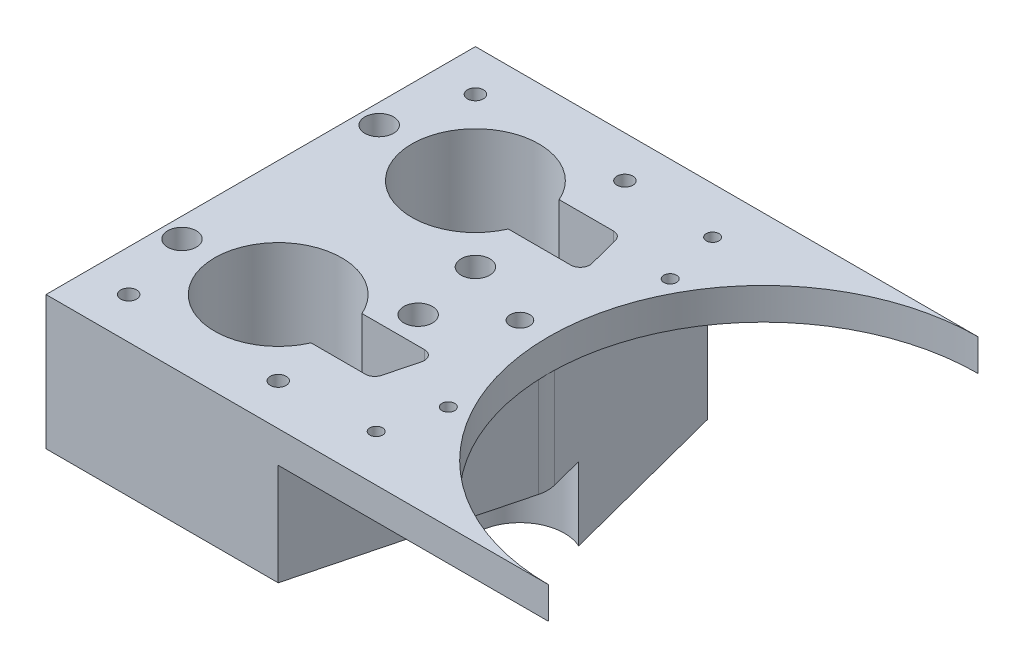
SolidWorks part; units mm, degrees
ref_plane "Alzado" through (0, 0, 0) normal (0, 0, 1) x (1, 0, 0)
ref_plane "Planta" through (0, 0, 0) normal (0, 1, 0) x (1, 0, 0)
ref_plane "Vista lateral" through (0, 0, 0) normal (1, 0, 0) x (0, 0, -1)
sketch "Croquis2" plane through (0, 0, 0) normal (0, 1, 0) x (1, 0, 0)
  line L0 (32.725, -35) -> (-35, -35) construction
  line L1 (52.1828, -19.7053) -> (38, 35) construction
  line L2 (-35, 35) -> (38, 35) construction
  line L3 (-35, -35) -> (-35, 35) construction
  line L4 (32.725, -35) -> (-35, -35)
  line L5 (52.1828, -19.7053) -> (38, 35)
  line L6 (-35, 35) -> (38, 35)
  line L7 (-35, -35) -> (-35, 35)
  arc A0 (32.5, -32.5) -> (54.1538, -20.7774) centre (46.5, -32.5) ccw construction
  arc A1 (52.1828, -19.7053) -> (32.5, -32.5) centre (46.5, -32.5) ccw construction
  arc A2 (32.5, -32.5) -> (32.725, -35) centre (46.5, -32.5) ccw
  arc A3 (52.1828, -19.7053) -> (32.5, -32.5) centre (46.5, -32.5) ccw
  circle A4 centre (1.5, -1.5) radius 24 construction
  circle A5 centre (1.5, -1.5) radius 24 construction
extrude "Saliente-Extruir2" add sketch "Croquis2" along normal blind 23
sketch "Croquis7" plane through (0, 23, 0) normal (0, 1, 0) x (1, 0, 0)
  circle A0 centre (1.5, -1.5) radius 24 construction
  circle A1 centre (1.5, -1.5) radius 24 construction
  circle A2 centre (1.5, -1.5) radius 20
  dimension "D1" = 40
extrude "Cortar-Extruir1" cut sketch "Croquis7" against normal blind 16 contours A2
sketch "Croquis8" plane through (0, 7, 0) normal (0, 1, 0) x (1, 0, 0)
  circle A0 centre (1.5, -1.5) radius 10.25
  circle A1 centre (1.5, -1.5) radius 20 construction
  dimension "D1" = 20.5
extrude "Cortar-Extruir2" cut sketch "Croquis8" against normal through all
sketch "Croquis9" plane through (0, 23, 0) normal (0, 1, 0) x (1, 0, 0)
  line L0 (-35, 35) -> (-35, -35) construction
  line L1 (38, 35) -> (-35, 35) construction
  line L2 (-35, 35) -> (-35, -100)
  line L4 (38, 35) -> (-35, 35)
  line L6 (46.5, -32.5) -> (-35, -32.5) construction
  line L7 (38, 35) -> (54.8494, -29.9904)
  line L9 (52.1828, -19.7053) -> (38, 35) construction
  line L10 (38, -100) -> (54.8494, -35.0096)
  line L11 (38, -100) -> (-35, -100)
  arc A0 (52.1828, -19.7053) -> (32.725, -35) centre (46.5, -32.5) ccw construction
  circle A2 centre (1.5, -1.5) radius 20 construction
  circle A3 centre (1.5, -1.5) radius 20
  arc A4 (52.1828, -19.7053) -> (32.725, -35) centre (46.5, -32.5) ccw construction
  circle A5 centre (46.5, -32.5) radius 3.075
  arc A6 (54.8494, -35.0096) -> (54.8494, -29.9904) centre (45.1694, -32.5) ccw
  circle A7 centre (1.5, -1.5) radius 10.25 construction
  circle A8 centre (1.5, -1.5) radius 10.25 construction
  circle A9 centre (1.5, -63.5) radius 10.25
  point P19 (55.5, -32.5)
  dimension "D1" = 10
  dimension "D2" = 6.15
extrude "Saliente-Extruir3" add sketch "Croquis9" along normal blind 32
sketch "Croquis10" plane through (0, 23, 0) normal (0, -1, 0) x (1, 0, 0)
  line L0 (46.5, 32.5) -> (-35, 32.5) construction
  line L1 (-35, -35) -> (-35, 35) construction
  circle A0 centre (1.5, 1.5) radius 20 construction
  circle A1 centre (1.5, 1.5) radius 20 construction
  circle A2 centre (1.5, 63.5) radius 20
extrude "Cortar-Extruir3" cut sketch "Croquis10" against normal through all from offset 7 offset against normal yes
sketch "Croquis11" plane through (0, 55, 0) normal (0, 1, 0) x (1, 0, 0)
  line L0 (46.5, -32.5) -> (123, -32.5) construction
  line L1 (38, 35) -> (-35, 35) construction
  line L2 (123, 35) -> (-35, 35)
  line L3 (-35, 35) -> (-35, -100)
  line L4 (-35, -100) -> (123, -100)
  arc A0 (123, -100) -> (123, 35) centre (123, -32.5) ccw
  circle A1 centre (46.5, -32.5) radius 3.075 construction
  circle A2 centre (1.5, -63.5) radius 20 construction
  circle A3 centre (1.5, -1.5) radius 20 construction
  circle A4 centre (46.5, -32.5) radius 3.075
  circle A5 centre (1.5, -63.5) radius 20
  circle A6 centre (1.5, -1.5) radius 20
  dimension "D1" = 76.5
extrude "Saliente-Extruir4" add sketch "Croquis11" along normal blind 20
sketch "Croquis12" plane through (0, 55, 0) normal (0, -1, 0) x (1, 0, 0)
  circle A0 centre (123, 32.5) radius 63
  dimension "D1" = 126
extrude "Cortar-Extruir4" cut sketch "Croquis12" against normal blind 3
sketch "Croquis13" plane through (0, 58, 0) normal (0, -1, 0) x (1, 0, 0)
  circle A0 centre (123, 32.5) radius 55
  circle A1 centre (123, 32.5) radius 63 construction
  dimension "D1" = 110
extrude "Cortar-Extruir5" cut sketch "Croquis13" against normal blind 10
sketch "Croquis14" plane through (0, 75, 0) normal (0, 1, 0) x (1, 0, 0)
  line L0 (-35, -100) -> (123, -100) construction
  line L1 (123, 35) -> (-35, 35) construction
  line L2 (-35, 35) -> (-35, -100) construction
  line L3 (-35, -100) -> (123, -100)
  line L4 (123, 35) -> (-35, 35)
  line L5 (-35, 35) -> (-35, -100)
  arc A0 (123, -100) -> (123, 35) centre (123, -32.5) ccw construction
  arc A1 (123, -100) -> (123, 35) centre (123, -32.5) ccw
extrude "Saliente-Extruir5" add sketch "Croquis14" along normal blind 10
chamfer "Chaflán1" distance 8 angle 30 3 edges at (44, 85, -35) (190.5, 85, 32.5) (44, 85, 100)
sketch "Croquis15" plane through (0, 68, 0) normal (0, -1, 0) x (1, 0, 0)
  circle A0 centre (123, 32.5) radius 6
  dimension "D1" = 12
extrude "Cortar-Extruir6" cut sketch "Croquis15" against normal blind 14.8
sketch "Croquis17" plane through (0, 0, 0) normal (0, -1, 0) x (1, 0, 0)
  line L0 (1.5, 1.5) -> (16.5, 1.5) construction
  line L1 (1.5, 1.5) -> (13.6244, 8.5) construction
  circle A0 centre (1.5, 1.5) radius 15 construction
  circle A1 centre (1.5, 1.5) radius 14 construction
  circle A2 centre (16.5, 1.5) radius 1.5
  circle A3 centre (-6, -11.4904) radius 1.5
  circle A4 centre (-6, 14.4904) radius 1.5
  circle A6 centre (13.6244, 8.5) radius 1.5
  circle A7 centre (1.5, -12.5) radius 1.5
  circle A8 centre (1.5, 1.5) radius 14 construction
  circle A9 centre (-10.6244, 8.5) radius 1.5
  circle A10 centre (1.5, 1.5) radius 14 construction
  point P13 (1.5, 1.5)
  point P22 (1.5, 1.5)
  dimension "D1" = 30
  dimension "D2" = 28
  dimension "D3" = 3
  dimension "D5" = 30
  dimension "D4" = 3
  dimension "D6" = 3
extrude "Cortar-Extruir7" cut sketch "Croquis17" against normal up to next
sketch "Croquis19" plane through (0, 23, 0) normal (0, -1, 0) x (1, 0, 0)
  line L0 (1.5, 63.5) -> (16.5, 63.5) construction
  line L1 (1.5, 63.5) -> (13.6244, 70.5) construction
  circle A0 centre (1.5, 63.5) radius 15 construction
  circle A1 centre (1.5, 63.5) radius 14 construction
  circle A2 centre (16.5, 63.5) radius 1.5
  circle A3 centre (-6, 50.5096) radius 1.5
  circle A4 centre (-6, 76.4904) radius 1.5
  circle A6 centre (13.6244, 70.5) radius 1.5
  circle A7 centre (1.5, 49.5) radius 1.5
  circle A8 centre (-10.6244, 70.5) radius 1.5
  point P13 (1.5, 63.5)
  point P20 (1.5, 63.5)
  dimension "D1" = 30
  dimension "D2" = 28
  dimension "D3" = 3
  dimension "D6" = 30
  dimension "D4" = 3
  dimension "D5" = 3
extrude "Cortar-Extruir9" cut sketch "Croquis19" against normal up to next
sketch "Croquis20" plane through (0, 0, 0) normal (0, -1, 0) x (1, 0, 0)
  line L1 (16.5, 1.5) -> (41.2646, 1.5) construction
  line L2 (46.3749, 21.211) -> (32.192, -33.4942)
  line L3 (42.3657, 5.7471) -> (39.7731, -4.2529)
  line L4 (39.4617, 9.5) -> (19.8303, 9.5)
  line L5 (36.8691, -6.5) -> (19.8303, -6.5)
  circle A0 centre (1.5, 1.5) radius 20 construction
  arc A1 (19.8303, -6.5) -> (19.8303, 9.5) centre (1.5, 1.5) ccw
  arc A2 (39.7731, -4.2529) -> (36.8691, -6.5) centre (36.8691, -3.5) cw
  arc A3 (42.3657, 5.7471) -> (39.4617, 9.5) centre (39.4617, 6.5) ccw
  dimension "D3" = 3
  dimension "D2" = 16
  dimension "D1" = 6
extrude "Cortar-Extruir10" cut sketch "Croquis20" against normal through all
sketch "Croquis21" plane through (0, 23, 0) normal (0, -1, 0) x (1, 0, 0)
  line L0 (19.8303, -6.5) -> (36.8691, -6.5) construction
  line L1 (39.7731, -4.2529) -> (42.3657, 5.7471) construction
  line L2 (39.4617, 9.5) -> (19.8303, 9.5) construction
  line L3 (19.8303, -6.5) -> (36.8691, -6.5) construction
  line L4 (39.7731, -4.2529) -> (42.3657, 5.7471) construction
  line L5 (39.4617, 9.5) -> (19.8303, 9.5) construction
  line L6 (46.5, 32.5) -> (-35, 32.5) construction
  line L7 (-35, -35) -> (-35, 35) construction
  line L8 (39.4617, 55.5) -> (19.8303, 55.5)
  line L9 (39.7731, 69.2529) -> (42.3657, 59.2529)
  line L10 (19.8303, 71.5) -> (36.8691, 71.5)
  arc A0 (36.8691, -6.5) -> (39.7731, -4.2529) centre (36.8691, -3.5) ccw construction
  arc A1 (42.3657, 5.7471) -> (39.4617, 9.5) centre (39.4617, 6.5) ccw construction
  arc A2 (19.8303, -6.5) -> (19.8303, 9.5) centre (1.5, 1.5) ccw construction
  arc A3 (36.8691, -6.5) -> (39.7731, -4.2529) centre (36.8691, -3.5) ccw construction
  arc A4 (42.3657, 5.7471) -> (39.4617, 9.5) centre (39.4617, 6.5) ccw construction
  arc A5 (19.8303, -6.5) -> (19.8303, 9.5) centre (1.5, 1.5) ccw construction
  arc A6 (19.8303, 71.5) -> (19.8303, 55.5) centre (1.5, 63.5) cw
  arc A7 (42.3657, 59.2529) -> (39.4617, 55.5) centre (39.4617, 58.5) cw
  arc A8 (36.8691, 71.5) -> (39.7731, 69.2529) centre (36.8691, 68.5) cw
extrude "Cortar-Extruir11" cut sketch "Croquis21" against normal blind 50
sketch "Croquis22" plane through (0, 0, 0) normal (0, -1, 0) x (1, 0, 0)
  circle A0 centre (-6, 14.4904) radius 3
  circle A1 centre (-10.6244, 8.5) radius 3
  circle A2 centre (-6, -11.4904) radius 3
  circle A3 centre (1.5, -12.5) radius 3
  circle A4 centre (16.5, 1.5) radius 3
  circle A5 centre (13.6244, 8.5) radius 3
  dimension "D1" = 6
extrude "Cortar-Extruir12" cut sketch "Croquis22" against normal blind 3
sketch "Croquis23" plane through (0, 23, 0) normal (0, -1, 0) x (1, 0, 0)
  circle A0 centre (-6, 76.4904) radius 3
  circle A1 centre (-10.6244, 70.5) radius 3
  circle A2 centre (-6, 50.5096) radius 3
  circle A3 centre (1.5, 49.5) radius 3
  circle A4 centre (16.5, 63.5) radius 3
  circle A5 centre (13.6244, 70.5) radius 3
  dimension "D1" = 6
extrude "Cortar-Extruir13" cut sketch "Croquis23" against normal blind 3
sketch "Croquis25" plane through (0, 23, 0) normal (0, -1, 0) x (1, 0, 0)
  line L0 (1.5, 63.5) -> (-35, 63.5) construction
  line L1 (-35, 35) -> (-35, 100) construction
  line L2 (-35, 35) -> (32.725, 35) construction
  circle A0 centre (-28.75, 63.5) radius 2.5
  circle A1 centre (29, 47) radius 2.5
  dimension "D1" = 5
  dimension "D2" = 6.25
  dimension "D3" = 64
  dimension "D4" = 12
extrude "Cortar-Extruir15" cut sketch "Croquis25" against normal through all
sketch "Croquis24" plane through (0, 0, 0) normal (0, -1, 0) x (1, 0, 0)
  line L0 (1.5, 1.5) -> (-35, 1.5) construction
  line L1 (-35, -35) -> (-35, 35) construction
  line L4 (-22, -22) -> (25, -22) construction
  line L5 (-22, -22) -> (-22, 25) construction
  line L6 (-22, 25) -> (25, 25) construction
  line L7 (25, -22) -> (25, 25) construction
  line L8 (-22, -22) -> (25, 25) construction
  line L9 (-22, 25) -> (25, -22) construction
  circle A0 centre (-28.75, 1.5) radius 2.5
  circle A1 centre (25, 25) radius 2.5
  dimension "D1" = 5
  dimension "D2" = 6.25
  dimension "D3" = 47
extrude "Cortar-Extruir14" cut sketch "Croquis24" against normal through all
sketch "Croquis26" plane through (0, 55, 0) normal (0, -1, 0) x (1, 0, 0)
  line L2 (49.616, 103.0115) -> (66.4653, 38.0212)
  line L3 (49.616, 103.0115) -> (66.4653, 38.0212) construction
  line L4 (-35, 95.3812) -> (123, 95.3812) construction
  line L5 (46.5, 32.5) -> (123, 32.5) construction
  circle A0 centre (54.1868, 85.3812) radius 2
  circle A1 centre (58.8535, 67.3812) radius 2
  circle A2 centre (58.8535, -2.3812) radius 2
  circle A3 centre (54.1868, -20.3812) radius 2
  dimension "D2" = 10
  dimension "D3" = 18
  dimension "D4" = 4
  dimension "D1" = 12
extrude "Cortar-Extruir16" cut sketch "Croquis26" against normal through all
sketch "Croquis27" plane through (0, 85, 0) normal (0, 1, 0) x (1, 0, 0)
  circle A0 centre (54.1868, 20.3812) radius 3.5
  circle A1 centre (58.8535, 2.3812) radius 3.5
  circle A2 centre (58.8535, -67.3812) radius 3.5
  circle A3 centre (54.1868, -85.3812) radius 3.5
  dimension "D1" = 7
extrude "Cortar-Extruir17" cut sketch "Croquis27" against normal blind 5
sketch "Croquis28" plane through (0, 55, 0) normal (0, -1, 0) x (1, 0, 0)
  line L0 (38, 100) -> (54.8494, 35.0096) construction
  line L1 (55.2228, 81.3853) -> (58.1654, 84.2804)
  line L2 (58.1654, 84.2804) -> (57.1294, 88.2764)
  line L3 (57.1294, 88.2764) -> (53.1508, 89.3771)
  line L4 (53.1508, 89.3771) -> (50.2082, 86.482)
  line L5 (50.2082, 86.482) -> (51.2442, 82.486)
  line L6 (51.2442, 82.486) -> (55.2228, 81.3853)
  line L7 (59.8894, 63.3853) -> (62.832, 66.2804)
  line L8 (62.832, 66.2804) -> (61.7961, 70.2764)
  line L9 (61.7961, 70.2764) -> (57.8175, 71.3771)
  line L10 (57.8175, 71.3771) -> (54.8749, 68.482)
  line L11 (54.8749, 68.482) -> (55.9109, 64.486)
  line L12 (55.9109, 64.486) -> (59.8894, 63.3853)
  line L13 (59.8894, 1.6147) -> (55.9109, 0.514)
  line L14 (55.9109, 0.514) -> (54.8749, -3.482)
  line L15 (54.8749, -3.482) -> (57.8175, -6.3771)
  line L16 (57.8175, -6.3771) -> (61.7961, -5.2764)
  line L17 (61.7961, -5.2764) -> (62.832, -1.2804)
  line L18 (62.832, -1.2804) -> (59.8894, 1.6147)
  line L19 (55.2228, -16.3853) -> (51.2442, -17.486)
  line L20 (51.2442, -17.486) -> (50.2082, -21.482)
  line L21 (50.2082, -21.482) -> (53.1508, -24.3771)
  line L22 (53.1508, -24.3771) -> (57.1294, -23.2764)
  line L23 (57.1294, -23.2764) -> (58.1654, -19.2804)
  line L24 (58.1654, -19.2804) -> (55.2228, -16.3853)
  line L25 (52.1828, 19.7053) -> (38, -35) construction
  circle A0 centre (54.1868, 85.3812) radius 3.575 construction
  circle A1 centre (58.8535, 67.3812) radius 3.575 construction
  circle A2 centre (58.8535, -2.3812) radius 3.575 construction
  circle A3 centre (54.1868, -20.3812) radius 3.575 construction
  dimension "D1" = 7.15
extrude "Cortar-Extruir18" cut sketch "Croquis28" against normal blind 3.25
sketch "Croquis29" plane through (0, 68, 0) normal (0, -1, 0) x (1, 0, 0)
  circle A0 centre (123, 32.5) radius 37.5 construction
  circle A1 centre (160.5, 32.5) radius 1.5
  circle A2 centre (141.75, 0.024) radius 1.5
  circle A3 centre (104.25, 0.024) radius 1.5
  circle A4 centre (85.5, 32.5) radius 1.5
  circle A5 centre (104.25, 64.976) radius 1.5
  circle A6 centre (141.75, 64.976) radius 1.5
  point P18 (123, 32.5)
  dimension "D1" = 75
  dimension "D2" = 3
  dimension "D3" = 6
extrude "Cortar-Extruir19" cut sketch "Croquis29" against normal blind 10
sketch "Croquis30" plane through (0, 55, 0) normal (0, -1, 0) x (1, 0, 0)
  circle A0 centre (123, 32.5) radius 67.5
  arc A1 (123, -35) -> (123, 100) centre (123, 32.5) ccw construction
extrude "Cortar-Extruir20" cut sketch "Croquis30" against normal through all both and the other way through all
sketch "Croquis31" plane through (0, 85, 0) normal (0, 1, 0) x (1, 0, 0)
  line L0 (46.5, -32.5) -> (-35, -32.5) construction
  line L1 (-22, -25) -> (25, -25) construction
  line L2 (-22, -25) -> (-22, 22) construction
  line L3 (-22, 22) -> (25, 22) construction
  line L4 (25, -25) -> (25, 22) construction
  line L5 (-22, -25) -> (25, 22) construction
  line L6 (-22, 22) -> (25, -25) construction
  line L7 (-35, 30.3812) -> (-35, -95.3812) construction
  circle A0 centre (-22, 22) radius 2.5
  circle A1 centre (25, 22) radius 2.5
  circle A2 centre (25, -87) radius 2.5
  circle A3 centre (-22, -87) radius 2.5
  point P0 (1.5, -1.5)
  dimension "D2" = 5
  dimension "D1" = 47
extrude "Cortar-Extruir21" cut sketch "Croquis31" against normal through all
sketch "Croquis32" plane through (0, 85, 0) normal (0, 1, 0) x (1, 0, 0)
  circle A0 centre (-22, 22) radius 4.5
  circle A1 centre (25, 22) radius 4.5
  circle A2 centre (-22, -87) radius 4.5
  circle A3 centre (25, -87) radius 4.5
  dimension "D1" = 9
extrude "Cortar-Extruir22" cut sketch "Croquis32" against normal blind 5
sketch "Croquis33" plane through (0, 0, -35) normal (0, 0, -1) x (-1, 0, 0)
  line L0 (35, 77) -> (35, 0) construction
  line L1 (35, 65) -> (-123, 65)
  line L2 (35, 65) -> (35, 85)
  line L3 (35, 85) -> (-123, 85)
  line L4 (-123, 65) -> (-123, 85)
  line L5 (-123, 77) -> (-123, 55) construction
  line L6 (-98.4601, 85) -> (35, 85) construction
  dimension "D1" = 20
extrude "Cortar-Extruir23" cut sketch "Croquis33" against normal through all
sketch "Croquis34" plane through (0, 65, 0) normal (0, 1, 0) x (1, 0, 0)
  circle A0 centre (-28.75, -63.5) radius 4.5
  dimension "D1" = 9
extrude "Cortar-Extruir24" cut sketch "Croquis34" against normal blind 12
sketch "Croquis35" plane through (0, 65, 0) normal (0, 1, 0) x (1, 0, 0)
  circle A0 centre (-28.75, -1.5) radius 4.5
  dimension "D1" = 9
extrude "Cortar-Extruir25" cut sketch "Croquis35" against normal blind 45
sketch "Croquis36" plane through (0, 65, 0) normal (0, 1, 0) x (1, 0, 0)
  circle A0 centre (29, -47) radius 4.5
  dimension "D1" = 9
extrude "Cortar-Extruir26" cut sketch "Croquis36" against normal offset from surface (23 mm away) 19 up to face at (-22, 23, 89.5)
sketch "Croquis37" plane through (0, 65, 0) normal (0, 1, 0) x (1, 0, 0)
  circle A0 centre (25, -25) radius 4.5
  dimension "D1" = 9
extrude "Cortar-Extruir27" cut sketch "Croquis37" against normal offset from surface (23.6 mm away) 41.4 up to face at (25, 0, -19.5)
sketch "Croquis38" plane through (0, 0, 0) normal (0, -1, 0) x (1, 0, 0)
  line L1 (-17.2369, -22) -> (-19.6184, -17.875)
  line L2 (-19.6184, -17.875) -> (-24.3816, -17.875)
  line L3 (-24.3816, -17.875) -> (-26.7631, -22)
  line L4 (-26.7631, -22) -> (-24.3816, -26.125)
  line L5 (-24.3816, -26.125) -> (-19.6184, -26.125)
  line L6 (-19.6184, -26.125) -> (-17.2369, -22)
  line L7 (29.7631, -22) -> (27.3816, -17.875)
  line L8 (27.3816, -17.875) -> (22.6184, -17.875)
  line L9 (22.6184, -17.875) -> (20.2369, -22)
  line L10 (20.2369, -22) -> (22.6184, -26.125)
  line L11 (22.6184, -26.125) -> (27.3816, -26.125)
  line L12 (27.3816, -26.125) -> (29.7631, -22)
  line L13 (-17.2369, 87) -> (-19.6184, 91.125)
  line L14 (-19.6184, 91.125) -> (-24.3816, 91.125)
  line L15 (-24.3816, 91.125) -> (-26.7631, 87)
  line L16 (-26.7631, 87) -> (-24.3816, 82.875)
  line L17 (-24.3816, 82.875) -> (-19.6184, 82.875)
  line L18 (-19.6184, 82.875) -> (-17.2369, 87)
  line L19 (29.7631, 87) -> (27.3816, 91.125)
  line L20 (27.3816, 91.125) -> (22.6184, 91.125)
  line L21 (22.6184, 91.125) -> (20.2369, 87)
  line L22 (20.2369, 87) -> (22.6184, 82.875)
  line L23 (22.6184, 82.875) -> (27.3816, 82.875)
  line L24 (27.3816, 82.875) -> (29.7631, 87)
  circle A0 centre (-22, -22) radius 4.125 construction
  circle A1 centre (25, -22) radius 4.125 construction
  circle A2 centre (-22, 87) radius 4.125 construction
  circle A3 centre (25, 87) radius 4.125 construction
  dimension "D1" = 8.25
extrude "Cortar-Extruir28" cut sketch "Croquis38" against normal offset from surface (35 mm away) 30 up to face at (20.5, 65, 25)
sketch "Croquis39" plane through (0, 0, 0) normal (0, -1, 0) x (1, 0, 0)
  line L0 (-14, 21.115) -> (-14, 30)
  line L1 (-35, 35) -> (32.725, 35) construction
  line L2 (-35, -35) -> (-35, 35) construction
  line L3 (-30, 14) -> (-30, 30)
  line L5 (-30, -30) -> (-30, 35)
  line L6 (38, -30) -> (-30, -30)
  line L7 (-30, -30) -> (-30, -14)
  line L8 (34.131, -30) -> (-30, -30)
  line L9 (-35, 30) -> (32.725, 30)
  line L10 (-30, 30) -> (-14, 30)
  line L11 (38.2791, -14) -> (21.115, -14)
  line L12 (47.3429, 20.9601) -> (33.16, -33.7452)
  line L13 (38.2791, -14) -> (34.131, -30)
  line L14 (38, -35) -> (-35, -35) construction
  line L15 (-30, -14) -> (-18.115, -14)
  line L16 (-30, 14) -> (-20.1506, 14)
  arc A0 (-14, 21.115) -> (-20.1506, 14) centre (1.5, 1.5) ccw
  arc A1 (-18.115, -14) -> (21.115, -14) centre (1.5, 1.5) ccw
  point P21 (-14.9661, 20.3967)
  dimension "D4" = 50
  dimension "D5" = 21
  dimension "D6" = 21
  dimension "D7" = 21
  dimension "D1" = 5
  dimension "D2" = 5
  dimension "D3" = 5
extrude "Cortar-Extruir29" cut sketch "Croquis39" against normal up to surface (23 mm away) up to face at (-22, 23, 87)
